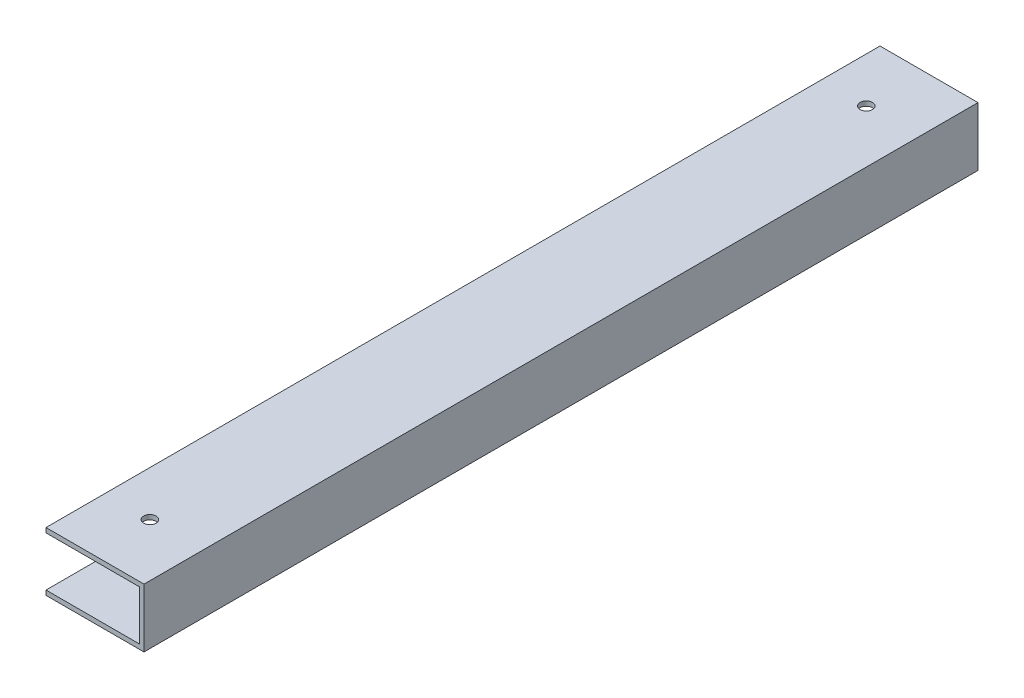
SolidWorks part; units mm, degrees
material "AISI 1020 Acero laminado en frío"
ref_plane "Alzado" through (0, 0, 0) normal (0, 0, 1) x (1, 0, 0)
ref_plane "Planta" through (0, 0, 0) normal (0, 1, 0) x (1, 0, 0)
ref_plane "Vista lateral" through (0, 0, 0) normal (1, 0, 0) x (0, 0, -1)
sketch "Croquis2" plane through (0, 0, 0) normal (0, 0, 1) x (1, 0, 0)
  line L1 (50, -30) -> (-50, -30)
  line L2 (50, -30) -> (50, 30)
  line L3 (50, 30) -> (-50, 30)
  line L4 (-50, -30) -> (-50, 30)
  line L5 (50, -30) -> (-50, 30) construction
  line L6 (50, 30) -> (-50, -30) construction
  point P0 (0, 0)
  point P6 (0, 30)
  dimension "D1" = 60
  dimension "D2" = 100
extrude "Saliente-Extruir1" add sketch "Croquis2" along normal mid plane 851
sketch "Croquis6" plane through (0, 0, 425.5) normal (0, 0, 1) x (1, 0, 0)
  line L4 (-50, 30) -> (-50, -30)
  line L5 (-50, -30) -> (50, -30)
  line L6 (50, -30) -> (50, 30)
  line L7 (50, 30) -> (-50, 30)
  line L8 (-50, 30) -> (-50, -30)
  line L9 (-50, -30) -> (50, -30)
  line L10 (50, -30) -> (50, 30)
  line L11 (50, 30) -> (-50, 30)
  line L16 (-45.2375, 25.2375) -> (-45.2375, -25.2375)
  line L17 (-45.2375, -25.2375) -> (45.2375, -25.2375)
  line L18 (45.2375, -25.2375) -> (45.2375, 25.2375)
  line L19 (45.2375, 25.2375) -> (-45.2375, 25.2375)
  line L20 (-45.2375, 25.2375) -> (-45.2375, -25.2375)
  line L21 (-45.2375, -25.2375) -> (45.2375, -25.2375)
  line L22 (45.2375, -25.2375) -> (45.2375, 25.2375)
  line L23 (45.2375, 25.2375) -> (-45.2375, 25.2375)
  dimension "D1" = 0
  dimension "D2" = 4.7625
extrude "Cortar-Extruir1" cut sketch "Croquis6" against normal blind 900 contours L22 L23 L20 L21
sketch "Croquis7" plane through (-50, 0, 0) normal (-1, 0, 0) x (0, 0, 1)
  line L0 (-425.5, 30) -> (-425.5, -30) construction
  line L1 (425.5, -25.2375) -> (-425.5, -25.2375)
  line L2 (425.5, -25.2375) -> (425.5, 25.2375)
  line L3 (425.5, 25.2375) -> (-425.5, 25.2375)
  line L4 (-425.5, -25.2375) -> (-425.5, 25.2375)
  line L5 (425.5, -25.2375) -> (-425.5, 25.2375) construction
  line L6 (425.5, 25.2375) -> (-425.5, -25.2375) construction
  line L7 (425.5, -30) -> (-425.5, -30) construction
  point P0 (0, 0)
  dimension "D1" = 4.7625
extrude "Cortar-Extruir2" cut sketch "Croquis7" against normal blind 20
sketch "Croquis8" plane through (0, 30, 0) normal (0, 1, 0) x (1, 0, 0)
  line L0 (-121.5247, 0) -> (93.3442, 0) construction
  line L1 (0, 497.4221) -> (0, -494.6167) construction
  line L4 (50, 425.5) -> (-50, 425.5) construction
  circle A0 centre (-4, 365.5) radius 6.35
  circle A1 centre (-4, -365.5) radius 6.35
  dimension "D1" = 12.7
  dimension "D2" = 60
  dimension "D3" = 4
extrude "Cortar-Extruir3" cut sketch "Croquis8" against normal blind 80
